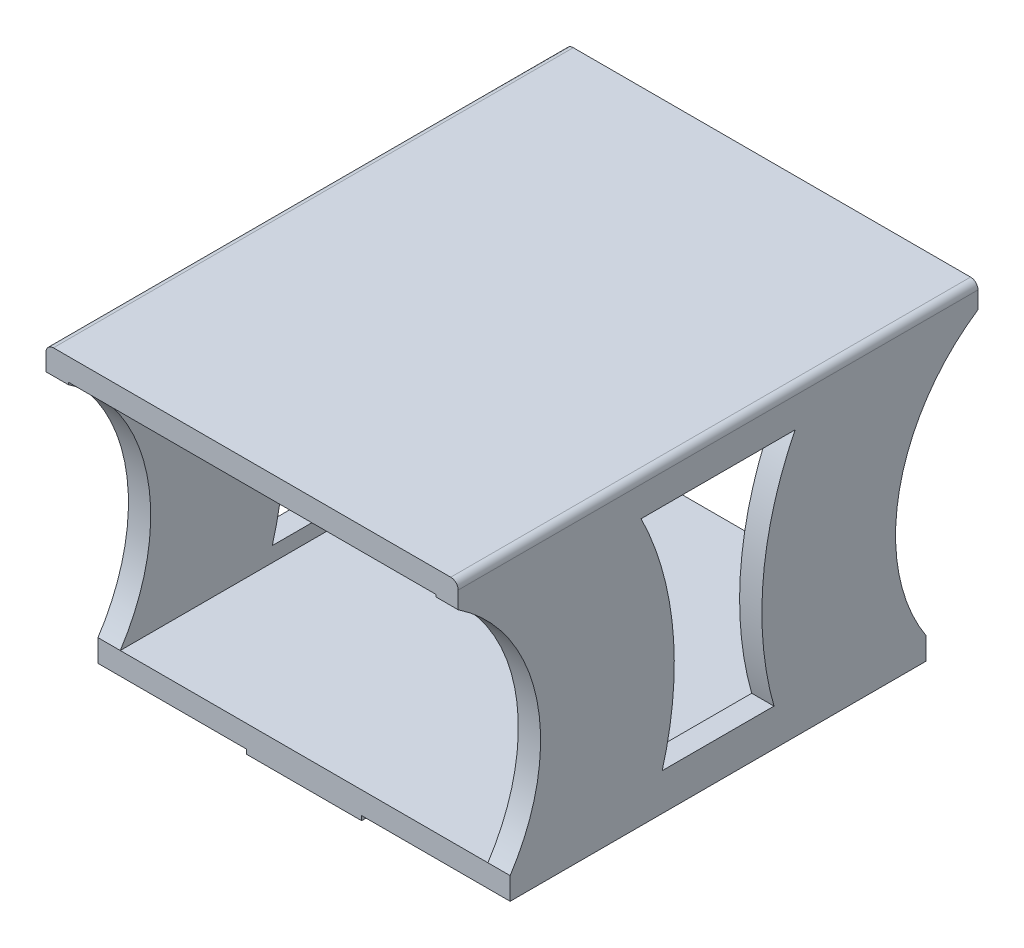
SolidWorks part; units mm, degrees
material "PLA"
ref_plane "Front Plane" through (0, 0, 0) normal (0, 0, 1) x (1, 0, 0)
ref_plane "Top Plane" through (0, 0, 0) normal (0, 1, 0) x (1, 0, 0)
ref_plane "Right Plane" through (0, 0, 0) normal (1, 0, 0) x (0, 0, -1)
sketch "Sketch1" plane through (0, 0, 0) normal (0, 1, 0) x (1, 0, 0)
  line L5 (-27.75, 28) -> (27.75, 28)
  line L6 (-27.75, 28) -> (-27.75, -28)
  line L7 (-27.75, -28) -> (27.75, -28)
  line L10 (27.75, 28) -> (27.75, -28)
  line L11 (-27.75, 28) -> (27.75, -28) construction
  line L16 (-27.75, -28) -> (27.75, 28) construction
  point P0 (0, 0)
  dimension "D1" = 55.5
  dimension "D2" = 56
extrude "Boss-Extrude1" add sketch "Sketch1" along normal blind 3
sketch "Sketch3" plane through (0, 0, 0) normal (0, 0, 1) x (1, 0, 0)
  line L0 (-27.75, 3) -> (-27.75, 40.8)
  line L1 (-27.75, 40.8) -> (27.75, 40.8)
  line L2 (27.75, 40.8) -> (27.75, 3)
  line L3 (27.75, 3) -> (24.75, 3)
  line L4 (-24.75, 3) -> (-27.75, 3)
  line L5 (-24.75, 37.8) -> (24.75, 37.8)
  line L6 (-24.75, 37.8) -> (-24.75, 3)
  line L8 (24.75, 37.8) -> (24.75, 3)
  dimension "D1" = 37.8
  dimension "D2" = 3
  dimension "D3" = 3
  dimension "D4" = 3
extrude "Boss-Extrude2" add sketch "Sketch3" along normal mid plane 56
sketch "Sketch4" plane through (0, 0, 0) normal (0, 0, 1) x (1, 0, 0)
  line L0 (-27.75, 40.8) -> (-27.75, 0) construction
  line L1 (27.75, 40.8) -> (-27.75, 40.8)
  line L2 (27.75, 40.8) -> (27.75, 37.5)
  line L3 (24.75, 37.8) -> (-24.75, 37.8)
  line L4 (-27.75, 40.8) -> (-27.75, 37.5)
  line L5 (-24.75, 37.8) -> (24.75, 37.8) construction
  line L6 (27.75, 40.8) -> (27.75, 0) construction
  line L8 (-27.75, 37.5) -> (-27.75, 3)
  line L9 (-27.75, 3) -> (-24.75, 3)
  line L10 (-24.75, 37.8) -> (-24.75, 3)
  line L12 (24.75, 37.8) -> (24.75, 3)
  line L13 (24.75, 3) -> (27.75, 3)
  line L14 (27.75, 37.5) -> (27.75, 3)
extrude "Boss-Extrude3" add sketch "Sketch4" along normal mid plane 70
sketch "Sketch5" plane through (0, 0, 0) normal (1, 0, 0) x (0, 0, -1)
  line L1 (-35, 40.8) -> (35, 40.8) construction
  line L2 (-35, 3) -> (-35, 40.8) construction
  line L3 (35, 3) -> (35, 40.8) construction
  line L4 (0, -11.506) -> (0, 59.4252) construction
  line L7 (-10.364, 35.8) -> (10.364, 35.8)
  line L8 (-7.5269, 5) -> (7.5269, 5)
  line L9 (-28, 0) -> (28, 0) construction
  line L10 (-35, 37.5) -> (-35, 3)
  line L11 (-35, 3) -> (-28, 3)
  line L12 (28, 3) -> (35, 3)
  line L13 (35, 3) -> (35, 37.5)
  arc A1 (-28, 3) -> (-35, 37.5) centre (-48.899, 16.7198) ccw
  arc A2 (28, 3) -> (35, 37.5) centre (48.899, 16.7198) cw
  arc A3 (-7.5269, 5) -> (-10.364, 35.8) centre (-48.899, 16.7198) ccw
  arc A4 (7.5269, 5) -> (10.364, 35.8) centre (48.899, 16.7198) cw
  dimension "D2" = 50
  dimension "D3" = 18
  dimension "D4" = 5
  dimension "D5" = 5
extrude "Cut-Extrude3" cut sketch "Sketch5" against normal through all both and the other way through all contours L8 A4 L7 A3 | A1 L10 L11 | L12 L13 A2
sketch "Sketch6" plane through (0, 0, 0) normal (0, -1, 0) x (1, 0, 0)
  line L0 (27.75, -28) -> (-27.75, -28) construction
  line L1 (-27.75, 28) -> (-7.75, 28) construction
  line L2 (-27.75, 28) -> (-27.75, -28) construction
  line L3 (-27.75, -28) -> (-7.75, -28) construction
  line L4 (-7.75, 28) -> (-7.75, -28) construction
  line L5 (0, 32.4399) -> (0, -32.5319) construction
  line L6 (27.75, -28) -> (7.75, -28) construction
  line L7 (27.75, 28) -> (27.75, -28) construction
  line L8 (27.75, 28) -> (7.75, 28) construction
  line L9 (7.75, 28) -> (7.75, -28) construction
  line L11 (-7.75, 28) -> (7.75, 28)
  line L12 (-7.75, 28) -> (-7.75, -28)
  line L13 (-7.75, -28) -> (7.75, -28)
  line L14 (7.75, 28) -> (7.75, -28)
  dimension "D2" = 20
extrude "Boss-Extrude4" add sketch "Sketch6" along normal blind 0.6
sketch "Sketch7" plane through (0, -0.6, 0) normal (0, -1, 0) x (1, 0, 0)
  circle A0 centre (0, 0) radius 7.1
  dimension "D1" = 14.2
extrude "Boss-Extrude5" add sketch "Sketch7" along normal blind 1.7
fillet "Fillet2" radius 1 2 edges at (27.75, 40.8, 0) (-27.75, 40.8, 0)
